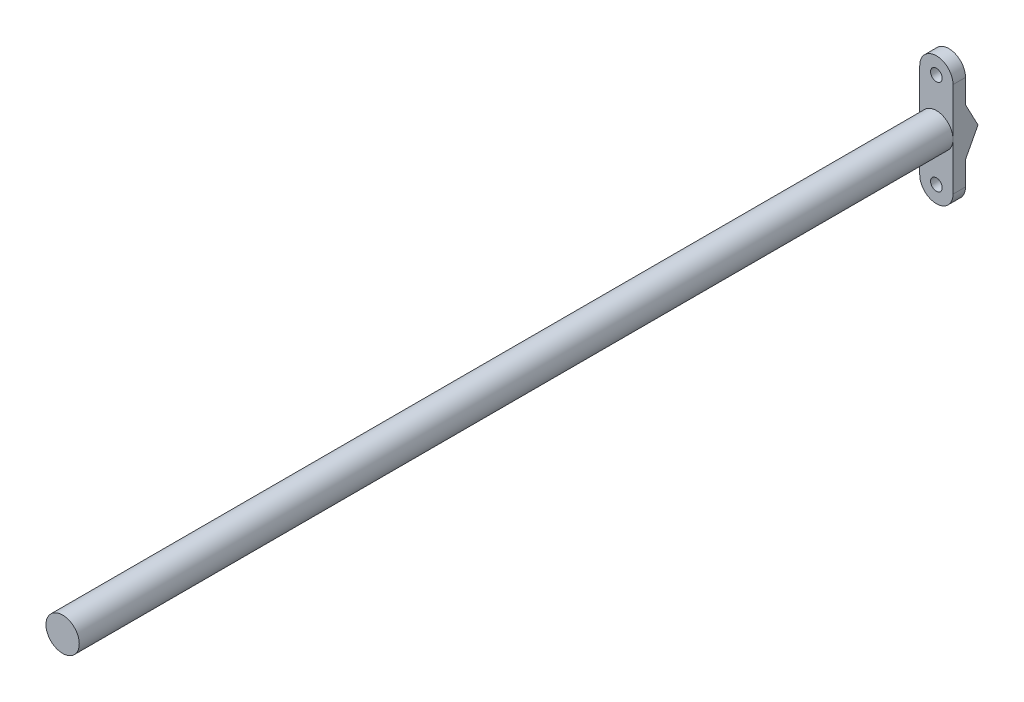
SolidWorks part; units mm, degrees
ref_plane "前视基准面" through (0, 0, 0) normal (0, 0, 1) x (1, 0, 0)
ref_plane "上视基准面" through (0, 0, 0) normal (0, 1, 0) x (1, 0, 0)
ref_plane "右视基准面" through (0, 0, 0) normal (1, 0, 0) x (0, 0, -1)
other "Configuration Table"
sketch "草图1" plane through (0, 0, 0) normal (0, 0, 1) x (1, 0, 0)
  line L0 (0, 0) -> (28.7629, 0) construction
  line L3 (-4, -11.4) -> (-4, 11.4)
  line L5 (4, -11.4) -> (4, 11.4)
  line L6 (-4, -14) -> (4, 14) construction
  line L7 (-4, 14) -> (4, -14) construction
  circle A0 centre (0, 11.4) radius 1.4
  circle A1 centre (0, -11.4) radius 1.4
  arc A2 (4, 11.4) -> (-4, 11.4) centre (0, 11.4) ccw
  arc A3 (-4, -11.4) -> (4, -11.4) centre (0, -11.4) ccw
  dimension "D1" = 2.8
  dimension "D3" = 4
  dimension "D2" = 11.4
  dimension "D4" = 8
extrude "凸台-拉伸1" add sketch "草图1" along normal blind 3
sketch "草图2" plane through (0, 0, 3) normal (0, 0, 1) x (1, 0, 0)
  circle A0 centre (0, 0) radius 4
  dimension "D1" = 8
extrude "凸台-拉伸3" add sketch "草图2" along normal blind 210
sketch "草图3" plane through (0, 0, 0) normal (0, 0, -1) x (-1, 0, 0)
  line L0 (-4, 0) -> (4, 0)
  line L1 (-4, -11.4) -> (-4, 11.4) construction
  line L2 (-4, 5.7) -> (4, 5.7)
  line L3 (4, 11.4) -> (4, -11.4) construction
  line L4 (-4, -5.7) -> (4, -5.7)
  line L5 (4, 5.7) -> (4, 0)
  line L6 (4, 0) -> (4, -5.7)
  line L7 (-4, -5.7) -> (-4, 0)
  line L8 (-4, 0) -> (-4, 5.7)
  line M5 (4, -11.4) -> (4, 11.4)
  line M7 (-4, 11.4) -> (-4, -11.4)
  dimension "D1" = 5.7
extrude "凸台-拉伸4" add sketch "草图3" along normal blind 3 contours L2 L0 M7 M5 | L4 L0 M7 M5
sketch "草图5" plane through (4, 0, 0) normal (1, 0, 0) x (0, 0, -1)
  line L0 (3, 0) -> (0, 5.7)
  line L1 (3, 5.7) -> (3, -5.7) construction
  line L2 (3, 0) -> (0, -5.7)
  line L3 (0, 5.7) -> (3, 5.7)
  line L4 (3, 5.7) -> (3, 0)
  line L5 (3, -5.7) -> (0, -5.7)
  line M2 (0, -5.7) -> (3, -5.7)
  line M3 (3, -5.7) -> (3, 5.7)
  line M4 (3, 5.7) -> (0, 5.7)
extrude "切除-拉伸1" cut sketch "草图5" against normal through all contours L0 M3 M4 | L2 M3 M2
